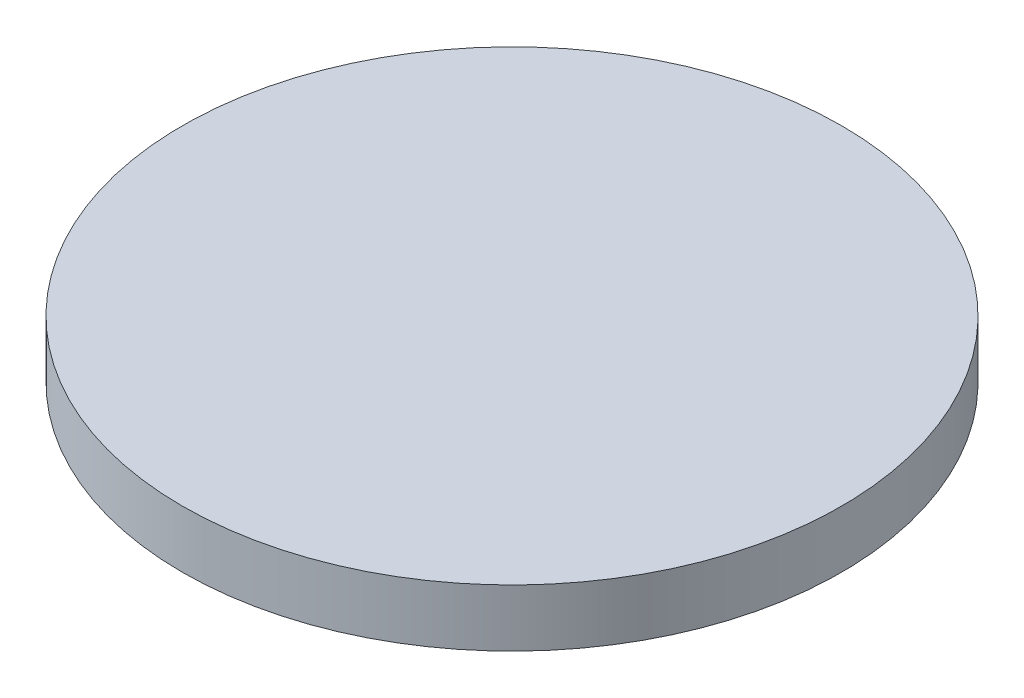
SolidWorks part; units mm, degrees
ref_plane "Plan de face" through (0, 0, 0) normal (0, 0, 1) x (1, 0, 0)
ref_plane "Plan de dessus" through (0, 0, 0) normal (0, 1, 0) x (1, 0, 0)
ref_plane "Plan de droite" through (0, 0, 0) normal (1, 0, 0) x (0, 0, -1)
sketch "Esquisse1" plane through (0, 0, 0) normal (0, 1, 0) x (1, 0, 0)
  circle A1 centre (0, 0) radius 11.5
  dimension "D2" = 23
extrude "Boss.-Extru.1" add sketch "Esquisse1" along normal blind 2
equation "\"0.1cl\"=0.05"
